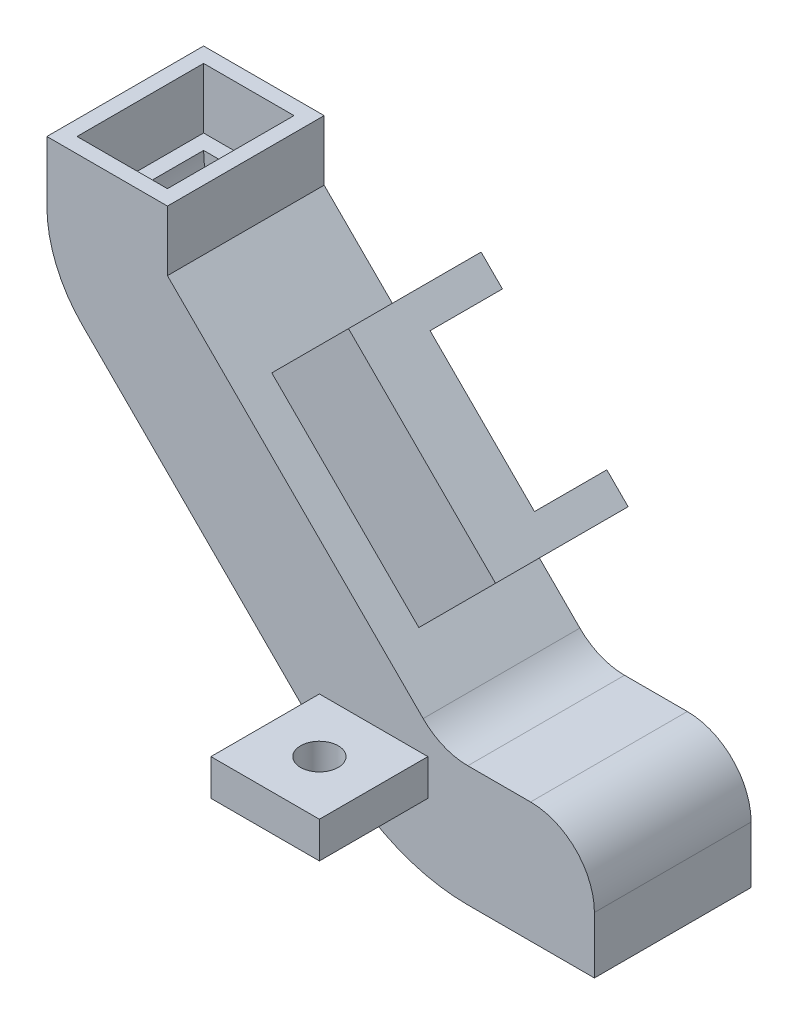
SolidWorks part; units mm, degrees
ref_plane "Front Plane" through (0, 0, 0) normal (0, 0, 1) x (1, 0, 0)
ref_plane "Top Plane" through (0, 0, 0) normal (0, 1, 0) x (1, 0, 0)
ref_plane "Right Plane" through (0, 0, 0) normal (1, 0, 0) x (0, 0, -1)
sketch "Sketch1" plane through (0, 0, 0) normal (0, 0, 1) x (1, 0, 0)
  line L0 (0, 0) -> (-44.5176, 44.5176) construction
  line L1 (-40.982, 48.0531) -> (-48.0531, 40.982) construction
  line L2 (-40.982, 48.0531) -> (1.4444, 5.6267)
  line L3 (12.3925, 6.0918) -> (22.8046, 6.0918)
  line L4 (-48.0531, 40.982) -> (-5.6267, -1.4444)
  line L5 (0, 0) -> (-7.0711, 0) construction
  line L6 (-40.982, 48.0531) -> (-37.4465, 51.5886) construction
  line L7 (-5.6267, -1.4444) -> (-9.1622, -4.9799) construction
  line L8 (12.3925, 1.0918) -> (22.8046, 1.0918)
  line L9 (-52.4465, 51.5886) -> (-57.4465, 51.5886)
  line L10 (-48.0531, 40.982) -> (-51.5886, 37.4465) construction
  line L11 (-51.5886, 37.4465) -> (-9.1622, -4.9799)
  line L12 (28.3925, -4.4961) -> (28.3925, -13.9082)
  line L13 (-42.4465, 51.5886) -> (-37.4465, 51.5886)
  line L14 (-37.4465, 51.5886) -> (4.9799, 9.1622)
  line L15 (4.9799, 9.1622) -> (1.4444, 5.6267) construction
  line L16 (12.3925, -8.9082) -> (12.3925, -13.9082)
  line L17 (12.3925, 16.5748) -> (4.9799, 9.1622) construction
  line L18 (-5.6267, -1.4444) -> (12.3925, 16.5748) construction
  line L19 (28.3925, -13.9082) -> (33.3925, -13.9082)
  line L20 (33.3925, -13.9082) -> (33.3925, -4.4961)
  arc A0 (-40.982, 48.0531) -> (-42.4465, 51.5886) centre (-37.4465, 51.5886) cw
  arc A1 (-5.6267, -1.4444) -> (12.3925, -8.9082) centre (12.3925, 16.5748) ccw
  arc A2 (-48.0531, 40.982) -> (-52.4465, 51.5886) centre (-37.4465, 51.5886) cw
  arc A3 (-9.1622, -4.9799) -> (12.3925, -13.9082) centre (12.3925, 16.5748) ccw
  arc A4 (-57.4465, 51.5886) -> (-51.5886, 37.4465) centre (-37.4465, 51.5886) ccw
  arc A5 (4.9799, 9.1622) -> (12.3925, 6.0918) centre (12.3925, 16.5748) ccw
  arc A6 (1.4444, 5.6267) -> (12.3925, 1.0918) centre (12.3925, 16.5748) ccw
  arc A7 (22.8046, 6.0918) -> (33.3925, -4.4961) centre (22.8046, -4.4961) cw
  arc A8 (22.8046, 1.0918) -> (28.3925, -4.4961) centre (22.8046, -4.4961) cw
  point P4 (-44.5176, 44.5176)
  dimension "D7" = 16
  dimension "D1" = 45
  dimension "D2" = 10
  dimension "D3" = 5
  dimension "D4" = 5
  dimension "D5" = 5
  dimension "D6" = 60
extrude "Boss-Extrude1" add sketch "Sketch1" along normal blind 16
sketch "Sketch5" plane through (0, 0, 16) normal (0, 0, 1) x (1, 0, 0)
  line L0 (-57.4465, 51.5886) -> (-37.4465, 51.5886)
  line L1 (-37.4465, 51.5886) -> (4.9799, 9.1622)
  line L2 (12.3925, 6.0918) -> (22.8046, 6.0918)
  line L3 (33.3925, -13.9082) -> (33.3925, -4.4961) construction
  line L4 (33.3925, -4.4961) -> (33.3925, -13.9082)
  line L5 (33.3925, -13.9082) -> (12.3925, -13.9082)
  line L6 (-9.1622, -4.9799) -> (-51.5886, 37.4465)
  arc A0 (4.9799, 9.1622) -> (12.3925, 6.0918) centre (12.3925, 16.5748) ccw
  arc A1 (22.8046, 6.0918) -> (33.3925, -4.4961) centre (22.8046, -4.4961) cw
  arc A2 (33.3925, -4.4961) -> (22.8046, 6.0918) centre (22.8046, -4.4961) ccw construction
  arc A3 (12.3925, -13.9082) -> (-9.1622, -4.9799) centre (12.3925, 16.5748) cw
  arc A4 (-51.5886, 37.4465) -> (-57.4465, 51.5886) centre (-37.4465, 51.5886) cw
extrude "Boss-Extrude4" add sketch "Sketch5" along normal blind 5
sketch "Sketch6" plane through (0, 0, 0) normal (0, 0, -1) x (-1, 0, 0)
  line L0 (-4.9799, 9.1622) -> (37.4465, 51.5886)
  line L1 (37.4465, 51.5886) -> (57.4465, 51.5886)
  line L2 (51.5886, 37.4465) -> (9.1622, -4.9799)
  line L3 (-12.3925, -13.9082) -> (-33.3925, -13.9082)
  line L4 (-33.3925, -13.9082) -> (-33.3925, -4.4961)
  line L5 (-22.8046, 6.0918) -> (-12.3925, 6.0918)
  line L6 (-22.8046, 6.0918) -> (-12.3925, 6.0918) construction
  line L7 (28.6077, 35.6787) -> (10.93, 18.001)
  line L8 (40.982, 48.0531) -> (-1.4444, 5.6267) construction
  line L9 (10.93, 18.001) -> (18.001, 10.93)
  line L10 (5.6267, -1.4444) -> (48.0531, 40.982) construction
  line L11 (18.001, 10.93) -> (35.6787, 28.6077)
  line L12 (35.6787, 28.6077) -> (28.6077, 35.6787)
  line L13 (40.982, 48.0531) -> (-1.4444, 5.6267) construction
  arc A0 (51.5886, 37.4465) -> (57.4465, 51.5886) centre (37.4465, 51.5886) ccw construction
  arc A1 (57.4465, 51.5886) -> (51.5886, 37.4465) centre (37.4465, 51.5886) cw
  arc A2 (9.1622, -4.9799) -> (-12.3925, -13.9082) centre (-12.3925, 16.5748) cw
  arc A3 (-33.3925, -4.4961) -> (-22.8046, 6.0918) centre (-22.8046, -4.4961) cw
  arc A4 (-12.3925, 6.0918) -> (-4.9799, 9.1622) centre (-12.3925, 16.5748) ccw construction
  arc A5 (-12.3925, 6.0918) -> (-4.9799, 9.1622) centre (-12.3925, 16.5748) ccw
  point P34 (19.7688, 26.8399)
  dimension "D1" = 25
extrude "Boss-Extrude5" add sketch "Sketch6" along normal blind 5
sketch "Sketch7" plane through (0, 51.5886, 0) normal (0, 1, 0) x (1, 0, 0)
  line L1 (-57.4465, 5) -> (-37.4465, 5)
  line L2 (-57.4465, 5) -> (-57.4465, -21)
  line L3 (-57.4465, -21) -> (-37.4465, -21)
  line L4 (-37.4465, 5) -> (-37.4465, -21)
  line L5 (-54.9465, 2.5) -> (-39.9465, 2.5)
  line L6 (-54.9465, 2.5) -> (-54.9465, -18.5)
  line L7 (-54.9465, -18.5) -> (-39.9465, -18.5)
  line L8 (-39.9465, 2.5) -> (-39.9465, -18.5)
  dimension "D1" = 2.5
  dimension "D2" = 2.5
  dimension "D3" = 2.5
  dimension "D4" = 2.5
extrude "Boss-Extrude6" add sketch "Sketch7" along normal blind 10
sketch "Sketch9" plane through (7.0711, 7.0711, 0) normal (0.7071, 0.7071, 0) x (0, 0, -1)
  line L0 (-15, 32.9573) -> (-5, 32.9573) construction
  line L1 (-15, 46.9573) -> (-5, 46.9573)
  line L2 (-15, 46.9573) -> (-15, 12.4573)
  line L3 (-15, 12.4573) -> (-5, 12.4573)
  line L4 (-5, 46.9573) -> (-5, 12.4573)
  line L5 (5, 62.9573) -> (5, 2.9573) construction
  point P8 (5, 32.9573)
  dimension "D1" = 34.5
  dimension "D2" = 20.5
  dimension "D3" = 10
  dimension "D4" = 10
extrude "Boss-Extrude7" add sketch "Sketch9" along normal blind 18
sketch "Sketch10" plane through (0, 0, 5) normal (0, 0, -1) x (-1, 0, 0)
  line L0 (20.8295, 45.5782) -> (17.2939, 42.0427)
  line L1 (13.4049, 53.0028) -> (26.1328, 40.2749) construction
  line L2 (17.2939, 42.0427) -> (9.8693, 49.4673)
  line L3 (-10.9903, 28.6077) -> (13.4049, 53.0028) construction
  line L4 (9.8693, 49.4673) -> (13.4049, 53.0028)
  line L5 (13.4049, 53.0028) -> (20.8295, 45.5782)
  line L6 (-10.9903, 28.6077) -> (-7.4548, 32.1432)
  line L7 (-7.4548, 32.1432) -> (-0.0302, 24.7186)
  line L8 (-0.0302, 24.7186) -> (-3.5657, 21.183)
  line L9 (-10.9903, 28.6077) -> (1.7376, 15.8797) construction
  line L10 (-3.5657, 21.183) -> (-10.9903, 28.6077)
  line L11 (-0.0302, 24.7186) -> (17.2939, 42.0427) construction
  line L13 (10.5764, 35.3252) -> (3.1518, 42.7498) construction
  line L14 (1.7376, 15.8797) -> (26.1328, 40.2749) construction
  point P20 (-3.7425, 28.4309)
  dimension "D1" = 5
  dimension "D2" = 5
  dimension "D3" = 10.5
  dimension "D5" = 15
  dimension "D6" = 7.5
extrude "Boss-Extrude8" add sketch "Sketch10" along normal blind 12
sketch "Sketch11" plane through (0, 0, -5) normal (0, 0, -1) x (-1, 0, 0)
  line L0 (19.7688, 26.8399) -> (14.3563, 32.2524) construction
  line L1 (40.982, 48.0531) -> (-1.4444, 5.6267) construction
  line L2 (24.365, 31.4361) -> (20.8295, 34.9716)
  line L3 (1.7376, 15.8797) -> (26.1328, 40.2749) construction
  line L5 (20.8295, 34.9716) -> (16.2333, 30.3754)
  line L6 (24.365, 31.4361) -> (19.7688, 26.8399)
  line L7 (9.8693, 49.4673) -> (17.2939, 42.0427) construction
  line L8 (16.2333, 30.3754) -> (9.5158, 23.6579)
  line L9 (9.5158, 23.6579) -> (13.0513, 20.1224)
  line L10 (13.0513, 20.1224) -> (19.7688, 26.8399)
  point P10 (11.2835, 21.8901)
  dimension "D1" = 6.5
  dimension "D2" = 9.5
extrude "Cut-Extrude3" cut sketch "Sketch11" against normal up to surface (10 mm away) up to face at (-8.1016, 33.911, 5)
sketch "Sketch12" plane through (0, 0, 21) normal (0, 0, 1) x (1, 0, 0)
  line L0 (16.0503, -1.9082) -> (-12.234, -1.9082) construction
  line L4 (-26.1328, 40.2749) -> (-1.7376, 15.8797) construction
  line L5 (-51.5886, 37.4465) -> (-9.1622, -4.9799) construction
  line L6 (-12.234, -1.9082) -> (5.766, -1.9082)
  line L7 (5.766, -1.9082) -> (5.766, 4.0918)
  line L8 (5.766, 4.0918) -> (-12.234, 4.0918)
  line L9 (-12.234, 4.0918) -> (-12.234, -1.9082)
  line L10 (12.3925, -13.9082) -> (33.3925, -13.9082) construction
  dimension "D1" = 18
  dimension "D2" = 6
  dimension "D3" = 12
extrude "Boss-Extrude9" add sketch "Sketch12" along normal blind 18
sketch "Sketch13" plane through (0, 4.0918, 0) normal (0, 1, 0) x (1, 0, 0)
  line L0 (5.766, -39) -> (-12.234, -39) construction
  line L1 (5.766, -39) -> (5.766, -21) construction
  circle A0 centre (-3.234, -30) radius 3.125
  point P5 (-3.234, -39)
  point P9 (5.766, -30)
  dimension "D1" = 6.25
extrude "Cut-Extrude4" cut sketch "Sketch13" against normal blind 18
sketch "Sketch14" plane through (0, 0, 0) normal (0, 1, 0) x (1, 0, 0)
  line L0 (28.3925, -8) -> (12.3925, -8) construction
  line L1 (12.3925, -21) -> (33.3925, -21) construction
  line L2 (28.3925, -16) -> (28.3925, 0) construction
  line L3 (-3.234, -30) -> (20.3925, -30) construction
  line L4 (12.3925, -16) -> (12.3925, 0) construction
  line L6 (20.3925, -8) -> (20.3925, -30) construction
  dimension "D1" = 23.6265
  dimension "D2" = 22
  dimension "D3" = 13
